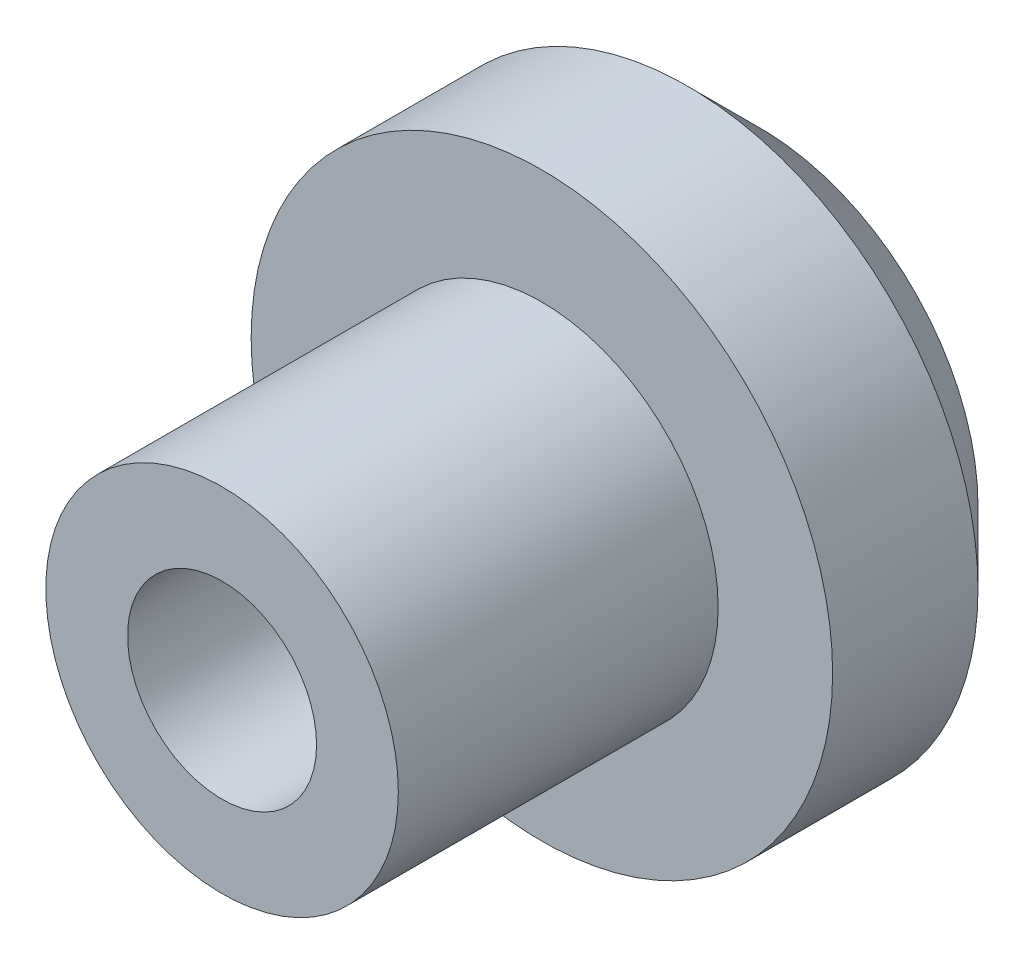
SolidWorks part; units mm, degrees
material "Copper"
ref_plane "Front Plane" through (0, 0, 0) normal (0, 0, 1) x (1, 0, 0)
ref_plane "Top Plane" through (0, 0, 0) normal (0, 1, 0) x (1, 0, 0)
ref_plane "Right Plane" through (0, 0, 0) normal (1, 0, 0) x (0, 0, -1)
sketch "Sketch1" plane through (0, 0, 0) normal (0, 0, 1) x (1, 0, 0)
  circle A0 centre (0, 0) radius 4
  dimension "D1" = 8
extrude "Boss-Extrude1" add sketch "Sketch1" along normal blind 3
sketch "Sketch2" plane through (0, 0, 3) normal (0, 0, 1) x (1, 0, 0)
  circle A0 centre (0, 0) radius 2.425
  dimension "D1" = 4.85
extrude "Boss-Extrude2" add sketch "Sketch2" along normal blind 4.4
sketch "Sketch3" plane through (0, 0, 7.4) normal (0, 0, 1) x (1, 0, 0)
  circle A0 centre (0, 0) radius 1.3
  dimension "D1" = 2.6
extrude "Cut-Extrude1" cut sketch "Sketch3" against normal through all
chamfer "Chamfer1" distance 1 angle 45 1 edges at (4, 0, 0)
